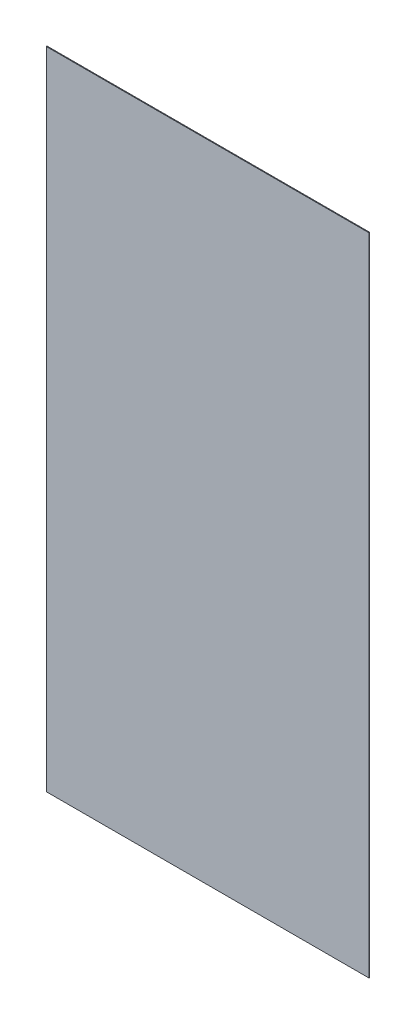
SolidWorks part; units mm, degrees
ref_plane "Front Plane" through (0, 0, 0) normal (0, 0, 1) x (1, 0, 0)
ref_plane "Top Plane" through (0, 0, 0) normal (0, 1, 0) x (1, 0, 0)
ref_plane "Right Plane" through (0, 0, 0) normal (1, 0, 0) x (0, 0, -1)
sketch "Sketch1" plane through (0, 0, 0) normal (0, 0, 1) x (1, 0, 0)
  line L1 (-609.6, -1219.2) -> (609.6, -1219.2)
  line L2 (-609.6, -1219.2) -> (-609.6, 1219.2)
  line L3 (-609.6, 1219.2) -> (609.6, 1219.2)
  line L4 (609.6, -1219.2) -> (609.6, 1219.2)
  line L5 (-609.6, -1219.2) -> (609.6, 1219.2) construction
  line L6 (-609.6, 1219.2) -> (609.6, -1219.2) construction
  point P0 (0, 0)
  dimension "D1" = 1219.2
  dimension "D2" = 2438.4
extrude "Boss-Extrude1" add sketch "Sketch1" along normal blind 3
